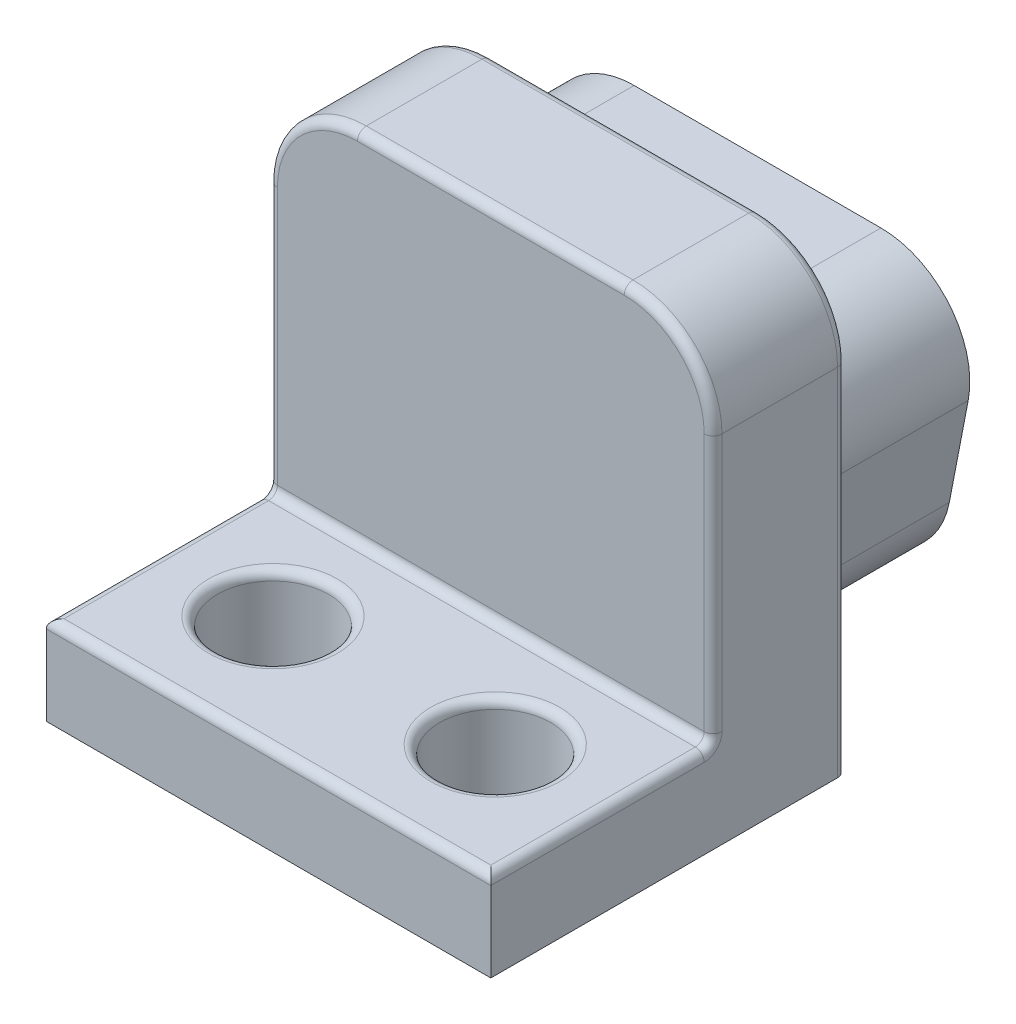
SolidWorks part; units mm, degrees
ref_plane "x/y" through (0, 0, 0) normal (0, 0, 1) x (1, 0, 0)
ref_plane "x/z" through (0, 0, 0) normal (0, 1, 0) x (1, 0, 0)
ref_plane "y/z" through (0, 0, 0) normal (1, 0, 0) x (0, 0, -1)
sketch "Sketch1" plane through (0, 0, 0) normal (0, 1, 0) x (1, 0, 0)
  line L1 (-10.16, -2.032) -> (2.54, -2.032)
  line L2 (-10.16, -2.032) -> (-10.16, 8.128)
  line L3 (-10.16, 8.128) -> (2.54, 8.128)
  line L4 (2.54, -2.032) -> (2.54, 8.128)
  point P3 (-3.81, 8.128)
  dimension "D1" = 12.7
  dimension "D2" = 10.16
  dimension "D3" = 2.032
  dimension "D4" = 10.16
extrude "Base-Extrude" add sketch "Sketch1" along normal blind 12.7
sketch "Sketch2" plane through (0, 0, -8.128) normal (0, 0, -1) x (-1, 0, 0)
  line L0 (3.81, 12.7) -> (3.81, -6.5379) construction
  line L1 (-2.54, 12.7) -> (10.16, 12.7) construction
  line L2 (0.8257, 2.286) -> (6.7943, 2.286)
  line L3 (9.2881, 4.3435) -> (9.8286, 7.1375)
  line L4 (7.3349, 10.16) -> (0.2851, 10.16)
  line L6 (-1.6681, 4.3435) -> (-2.2086, 7.1375)
  line L7 (-2.54, 0) -> (10.16, 0) construction
  arc A0 (9.2881, 4.3435) -> (6.7943, 2.286) centre (6.7943, 4.826) cw
  arc A1 (7.3349, 10.16) -> (9.8286, 7.1375) centre (7.3349, 7.62) cw
  arc A2 (0.2851, 10.16) -> (-2.2086, 7.1375) centre (0.2851, 7.62) ccw
  arc A3 (-1.6681, 4.3435) -> (0.8257, 2.286) centre (0.8257, 4.826) ccw
  point P4 (3.81, 10.16)
  point P12 (8.89, 2.286)
  point P21 (3.81, 2.286)
  dimension "D5" = 2.54
  dimension "D1" = 2.286
  dimension "D2" = 2.54
  dimension "D3" = 100.95
  dimension "D4" = 5.08
extrude "Boss-Extrude1" add sketch "Sketch2" along normal blind 3.81
sketch "Sketch4" plane through (0, 0, -11.938) normal (0, 0, -1) x (-1, 0, 0)
  line L0 (10.16, 12.7) -> (10.16, 0) construction
  line L2 (-2.54, 12.7) -> (10.16, 12.7) construction
  circle A0 centre (8.128, 7.62) radius 0.635
  dimension "D1" = 1.27
  dimension "D2" = 2.032
  dimension "D3" = 5.08
extrude "Cut-Extrude1" cut sketch "Sketch4" against normal blind 5.08
sketch "Sketch5" plane through (0, 0, -11.938) normal (0, 0, -1) x (-1, 0, 0)
  line L0 (10.16, 12.7) -> (10.16, 0) construction
  line L2 (-2.54, 0) -> (10.16, 0) construction
  circle A0 centre (6.858, 5.08) radius 0.635
  circle A1 centre (8.128, 7.62) radius 0.635 construction
  dimension "D2" = 5.08
  dimension "D1" = 3.302
extrude "Cut-Extrude2" cut sketch "Sketch5" against normal blind 5.08
sketch "Sketch6" plane through (0, 0, 0) normal (0, -1, 0) x (1, 0, 0)
  line L0 (-10.16, -8.128) -> (-10.16, 2.032) construction
  circle A0 centre (-5.08, 0) radius 0.3556
  dimension "D1" = 0.7112
  dimension "D2" = 5.08
extrude "Boss-Extrude2" add sketch "Sketch6" along normal blind 0.254
pattern_linear "LPattern1" count 2 spacing 2.7686 along (1, 0, 0) of "Boss-Extrude2"
pattern_linear "LPattern2" count 4 spacing 2.7686 along (1, 0, 0) of "Cut-Extrude1"
pattern_linear "LPattern3" count 3 spacing 2.7686 along (1, 0, 0) of "Cut-Extrude2"
sketch "Sketch7" plane through (0, 0, 0) normal (0, -1, 0) x (1, 0, 0)
  line L1 (-10.16, -8.128) -> (-10.16, 2.032) construction
  circle A0 centre (-5.08, -2.54) radius 0.3556
  dimension "D1" = 0.7112
  dimension "D2" = 5.08
  dimension "D3" = 2.54
extrude "Boss-Extrude3" add sketch "Sketch7" along normal up to surface (0.254 mm away) up to face at (-5.08, -0.254, -0.3556)
pattern_linear "LPattern4" count 2 spacing 2.7686 along (1, 0, 0) of "Boss-Extrude3"
ref_plane "Plane1" through (-3.81, 0, 0) normal (1, 0, 0) x (0, 0, -1)
sketch "Sketch9" plane through (0, 0, 2.032) normal (0, 0, 1) x (1, 0, 0)
  line L1 (-10.16, 12.7) -> (-3.8049, 12.7)
  line L2 (-10.16, 12.7) -> (-10.16, 2.54)
  line L3 (-10.16, 2.54) -> (-3.8049, 2.54)
  line L4 (-3.8049, 12.7) -> (-3.8049, 2.54)
  dimension "D1" = 10.16
  dimension "D2" = 6.3551
extrude "Cut-Extrude3" cut sketch "Sketch9" against normal blind 6.35
sketch "Sketch11" plane through (0, 2.54, 0) normal (0, 1, 0) x (-1, 0, 0)
  line L0 (10.16, 2.032) -> (3.8049, 2.032) construction
  line L1 (10.16, -4.318) -> (10.16, 2.032) construction
  circle A0 centre (6.985, -1.27) radius 1.5875
  point P2 (6.9825, 2.032)
  dimension "D1" = 3.175
  dimension "D2" = 3.302
  dimension "D3" = 3.175
extrude "Cut-Extrude4" cut sketch "Sketch11" against normal through all
mirror "Mirror1" about plane through (-3.81, 0, 0) normal (1, 0, 0) of "Cut-Extrude4", "Cut-Extrude3"
fillet "Fillet1" radius 2.54 2 edges at (-10.16, 12.7, -6.223) (2.54, 12.7, -6.223)
fillet "Fillet2" radius 0.254 16 edges at (2.54, 2.54, -1.143) (-0.635, 2.54, 0.3175) (-3.81, 12.7, -4.318) (-3.81, 12.7, -8.128) (-10.16, 6.35, -4.318) (2.54, 6.35, -4.318) (1.7961, 11.9561, -4.318) (-9.4161, 11.9561, -4.318) (-10.16, 5.08, -8.128) (2.54, 5.08, -8.128) (1.7961, 11.9561, -8.128) (-9.4161, 11.9561, -8.128) (-10.16, 2.54, -1.143) (-3.81, 2.54, -4.318) (-3.81, 2.54, 2.032) (-6.985, 2.54, 0.3175)
fillet "Filete1" radius 0.254 7 edges at (-1.9558, 5.08, -11.938) (-4.7244, 5.08, -11.938) (-7.493, 5.08, -11.938) (-8.763, 7.62, -11.938) (-5.9944, 7.62, -11.938) (-0.4572, 7.62, -11.938) (-3.2258, 7.62, -11.938)
